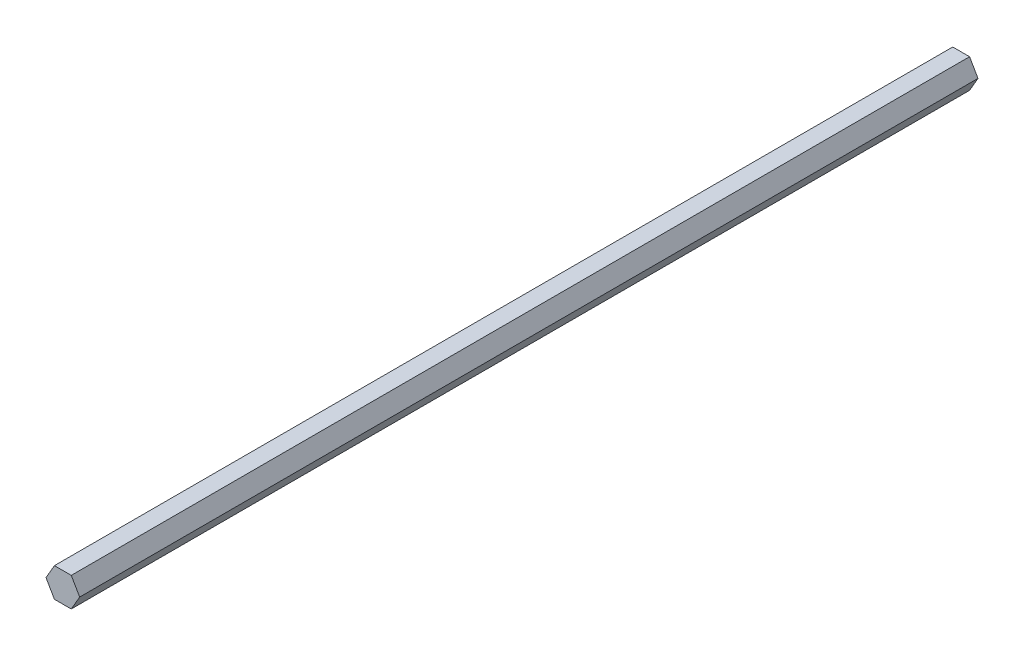
SolidWorks part; units mm, degrees
material "7075-T6 (SN)"
ref_plane "Front Plane" through (0, 0, 0) normal (0, 0, 1) x (1, 0, 0)
ref_plane "Top Plane" through (0, 0, 0) normal (0, 1, 0) x (1, 0, 0)
ref_plane "Right Plane" through (0, 0, 0) normal (1, 0, 0) x (0, 0, -1)
sketch "Sketch1" plane through (0, 0, 0) normal (0, 0, 1) x (1, 0, 0)
  line L1 (7.3323, 0) -> (3.6662, 6.35)
  line L2 (3.6662, 6.35) -> (-3.6662, 6.35)
  line L3 (-3.6662, 6.35) -> (-7.3323, 0)
  line L4 (-7.3323, 0) -> (-3.6662, -6.35)
  line L5 (-3.6662, -6.35) -> (3.6662, -6.35)
  line L6 (3.6662, -6.35) -> (7.3323, 0)
  circle A0 centre (0, 0) radius 6.35 construction
  dimension "D1" = 12.7
extrude "Boss-Extrude1" add sketch "Sketch1" along normal blind 391.16
